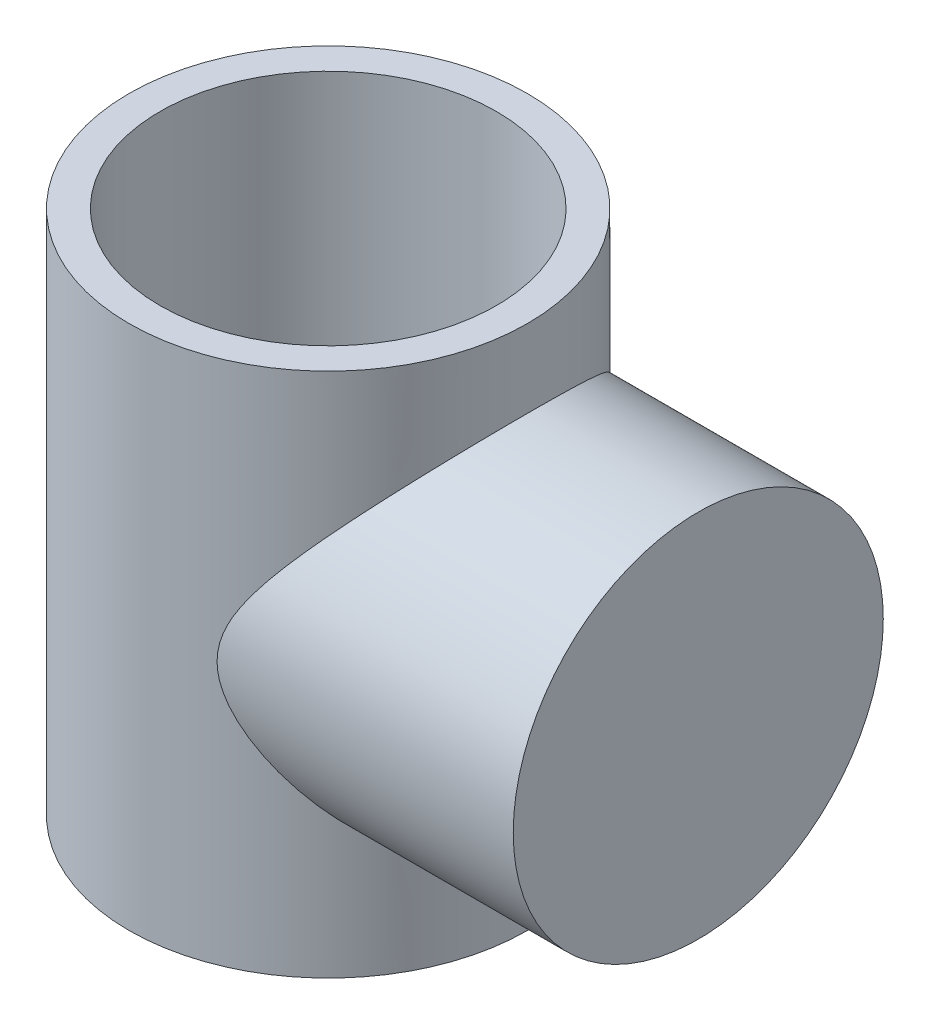
SolidWorks part; units mm, degrees
ref_plane "Front Plane" through (0, 0, 0) normal (1, 0, 0) x (0, 1, 0)
ref_plane "Top Plane" through (0, 0, 0) normal (0, 0, 1) x (0, 1, 0)
ref_plane "Right Plane" through (0, 0, 0) normal (0, 1, 0) x (-1, 0, 0)
sketch "Sketch1" plane through (0, 0, 0) normal (1, 0, 0) x (0, 1, 0)
  circle A0 centre (0, 0) radius 4.4
  dimension "D1" = 8.8
extrude "Boss-Extrude1" add sketch "Sketch1" along normal blind 8.8
sketch "Sketch2" plane through (0, 0, 0) normal (0, 1, 0) x (-1, 0, 0)
  circle A0 centre (0, 0) radius 4.7377
  circle A1 centre (0, 0) radius 4
  dimension "D1" = 8
extrude "Boss-Extrude2" add sketch "Sketch2" along normal mid plane 12.5
sketch "Sketch3" plane through (0, 0, 0) normal (0, 1, 0) x (-1, 0, 0)
  circle A0 centre (0, 0) radius 4 construction
  circle A1 centre (0, 0) radius 4
extrude "Cut-Extrude1" cut sketch "Sketch3" against normal through all both and the other way through all
